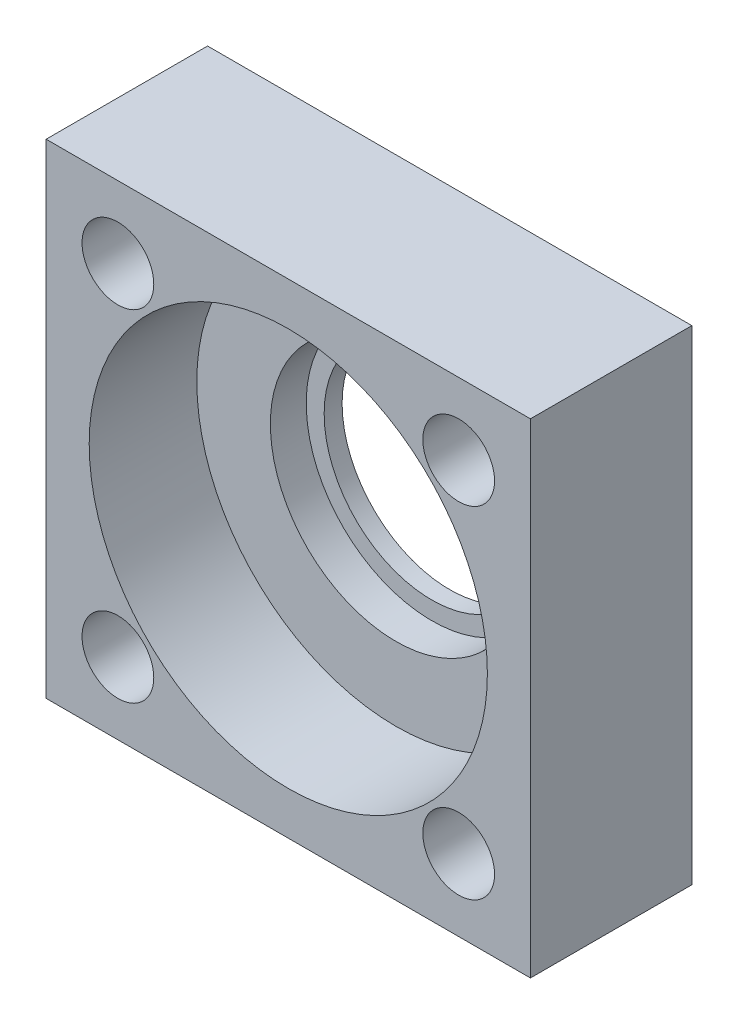
SolidWorks part; units mm, degrees
ref_plane "Front Plane" through (0, 0, 0) normal (0, 0, 1) x (1, 0, 0)
ref_plane "Top Plane" through (0, 0, 0) normal (0, 1, 0) x (1, 0, 0)
ref_plane "Right Plane" through (0, 0, 0) normal (1, 0, 0) x (0, 0, -1)
sketch "Sketch1" plane through (0, 0, 0) normal (0, 0, 1) x (1, 0, 0)
  line L1 (-67.5, -67.5) -> (67.5, -67.5)
  line L2 (-67.5, -67.5) -> (-67.5, 67.5)
  line L3 (-67.5, 67.5) -> (67.5, 67.5)
  line L4 (67.5, -67.5) -> (67.5, 67.5)
  line L5 (-67.5, -67.5) -> (67.5, 67.5) construction
  line L6 (-67.5, 67.5) -> (67.5, -67.5) construction
  point P0 (0, 0)
  dimension "D1" = 135
extrude "Boss-Extrude1" add sketch "Sketch1" along normal blind 45
sketch "Sketch2" plane through (0, 0, 45) normal (0, 0, 1) x (1, 0, 0)
  line L0 (67.5, 67.5) -> (-67.5, 67.5) construction
  line L1 (-67.5, 67.5) -> (-67.5, -67.5) construction
  line L2 (0, 70.0254) -> (0, -71.2554) construction
  line L3 (-71.6947, 0) -> (74.1548, 0) construction
  circle A0 centre (-47.5, 47.5) radius 10
  circle A1 centre (47.5, 47.5) radius 10
  circle A2 centre (47.5, -47.5) radius 10
  circle A3 centre (-47.5, -47.5) radius 10
  circle A4 centre (0, 0) radius 30
  dimension "D3" = 60
  dimension "D4" = 20
  dimension "D1" = 20
  dimension "D2" = 20
extrude "Cut-Extrude1" cut sketch "Sketch2" against normal through all
sketch "Sketch3" plane through (0, 0, 45) normal (0, 0, 1) x (1, 0, 0)
  circle A0 centre (0, 0) radius 55.5
  dimension "D1" = 111
extrude "Cut-Extrude2" cut sketch "Sketch3" against normal blind 30
sketch "Sketch4" plane through (0, 0, 15) normal (0, 0, 1) x (1, 0, 0)
  circle A0 centre (0, 0) radius 35
  dimension "D1" = 70
extrude "Cut-Extrude3" cut sketch "Sketch4" against normal blind 10 contours A0
